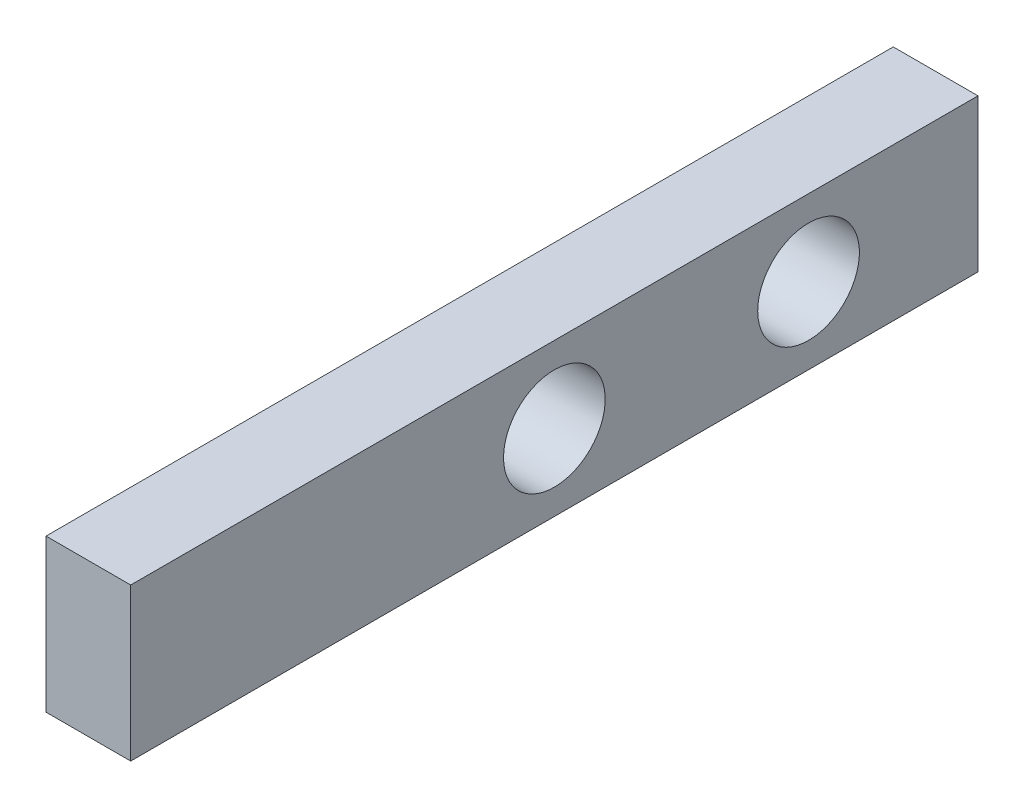
SolidWorks part; units mm, degrees
other "Preload Hard Stop"
ref_plane "Front Plane" through (0, 0, 0) normal (0, 0, 1) x (1, 0, 0)
ref_plane "Top Plane" through (0, 0, 0) normal (0, 1, 0) x (1, 0, 0)
ref_plane "Right Plane" through (0, 0, 0) normal (1, 0, 0) x (0, 0, -1)
sketch3d "Stop plate blank sketch datum points"
  point P0 (23.7083, -63.2, -38)
  point P1 (33.7083, -63.2, -38)
  point P2 (23.7083, -53.2, -38)
ref_plane "Stop plate blank sketch plane" through (0, 0, -38) normal (0, 0, 1) x (1, 0, 0)
sketch "Stop plate blank sketch" plane through (0, 0, -38) normal (0, 0, 1) x (1, 0, 0)
  line L0 (23.7083, -63.2) -> (25.7083, -63.2)
  line L1 (25.7083, -63.2) -> (25.7083, -59.6)
  line L2 (25.7083, -59.6) -> (23.7083, -59.6)
  line L3 (23.7083, -59.6) -> (23.7083, -63.2)
extrude "Stop plate blank" add sketch "Stop plate blank sketch" along normal blind 20 separate body
sketch3d "M2 stop clearance 1 sketch datum points"
  point P0 (23.6083, -61.4, -34)
  point P1 (23.6083, -51.4, -34)
  point P2 (23.6083, -61.4, -24)
ref_plane "M2 stop clearance 1 sketch plane" through (23.6083, 0, 0) normal (1, 0, 0) x (0, 0, -1)
sketch "M2 stop clearance 1 sketch" plane through (23.6083, 0, 0) normal (1, 0, 0) x (0, 0, -1)
  circle A0 centre (34, -61.4) radius 1.2
extrude "M2 stop clearance 1" cut sketch "M2 stop clearance 1 sketch" along normal blind 2.2
sketch3d "M2 stop clearance 2 sketch datum points"
  point P0 (23.6083, -61.4, -28)
  point P1 (23.6083, -51.4, -28)
  point P2 (23.6083, -61.4, -18)
ref_plane "M2 stop clearance 2 sketch plane" through (23.6083, 0, 0) normal (1, 0, 0) x (0, 0, -1)
sketch "M2 stop clearance 2 sketch" plane through (23.6083, 0, 0) normal (1, 0, 0) x (0, 0, -1)
  circle A0 centre (28, -61.4) radius 1.2
extrude "M2 stop clearance 2" cut sketch "M2 stop clearance 2 sketch" along normal blind 2.2
